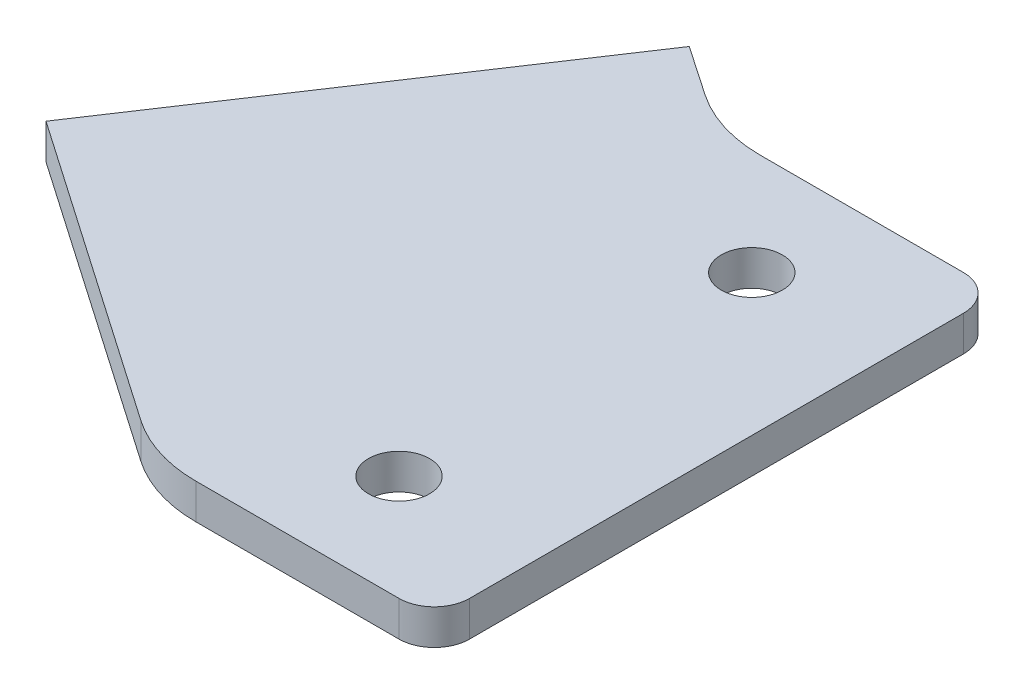
SolidWorks part; units mm, degrees
material "AISI 4340 Steel, annealed"
ref_plane "X-Y Datum" through (0, 0, 0) normal (0, 0, 1) x (1, 0, 0)
ref_plane "X-Z Datum" through (0, 0, 0) normal (0, 1, 0) x (1, 0, 0)
ref_plane "Y-Z Datum" through (0, 0, 0) normal (1, 0, 0) x (0, 0, -1)
sketch "Sketch1" plane through (0, 0, 0) normal (0, 1, 0) x (1, 0, 0)
  line L0 (-12.7, -25.4) -> (-43.5523, -4.0916)
  line L1 (-12.7, 25.4) -> (12.7, 25.4)
  line L2 (-12.7, 25.4) -> (-12.7, -25.4)
  line L3 (-12.7, -25.4) -> (12.7, -25.4)
  line L4 (12.7, 25.4) -> (12.7, -25.4)
  line L5 (-12.7, 25.4) -> (-20.429, 30.6758)
  line L6 (-20.429, 30.6758) -> (-43.5523, -4.0916)
  point P0 (0, -25.4)
  point P5 (-12.7, 0)
  dimension "D1" = 25.4
  dimension "D2" = 50.8
extrude "Boss-Extrude1" add sketch "Sketch1" along normal blind 3.175 contours L5 L6 L0 L2 | L4 L1 L2 L3
hole_wizard "M5 Clearance Hole1" positions "Sketch4" profile "Sketch5" hole size "M5" standard "ANSI Metric"
sketch "Sketch4" plane through (0, 0, 0) normal (0, -1, 0) x (-1, 0, 0)
  line L0 (0, 15.875) -> (0, -15.875) construction
  point P0 (0, 15.875)
  point P2 (0, -15.875)
  point P9 (0, 0)
  dimension "D1" = 31.75
sketch "Sketch5" plane through (0, 0, -15.875) normal (1, 0, 0) x (0, 0, -1)
  line L0 (0, 0) -> (0, 14.3524)
  line L1 (0, 14.3524) -> (2.75, 12.7)
  line L2 (2.75, 12.7) -> (2.75, 0)
  line L5 (2.75, 0) -> (0, 0)
  line L10 (0, 14.3524) -> (-2.75, 12.7) construction
  line L11 (0, -6.35) -> (0, 107.95) construction
  dimension "Hole Dia." = 5.5
  dimension "Hole Depth" = 12.7
  dimension "Drill Angle" = 118
fillet "Fillet1" radius 12.7 2 edges at (-12.7, 1.5875, 25.4) (-12.7, 1.5875, -25.4)
fillet "Fillet2" radius 3.175 2 edges at (12.7, 1.5875, 25.4) (12.7, 1.5875, -25.4)
